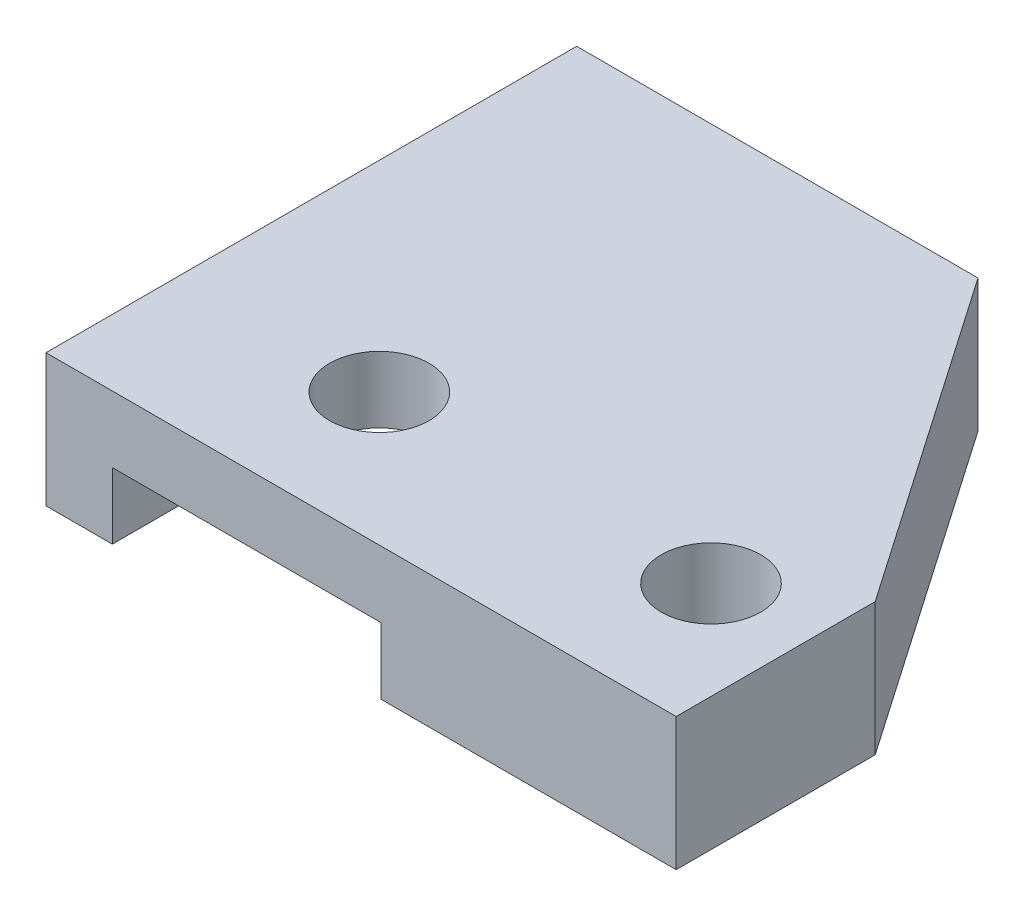
SolidWorks part; units mm, degrees
material "ABS"
ref_plane "Plan de face" through (0, 0, 0) normal (0, 0, 1) x (1, 0, 0)
ref_plane "Plan de dessus" through (0, 0, 0) normal (0, 1, 0) x (1, 0, 0)
ref_plane "Plan de droite" through (0, 0, 0) normal (1, 0, 0) x (0, 0, -1)
sketch "Esquisse1" plane through (0, 0, 0) normal (0, 0, 1) x (1, 0, 0)
  line L0 (10.1, -4) -> (19, -4)
  line L1 (0, 0) -> (19, 0)
  line L2 (0, 0) -> (0, -4)
  line L3 (0, -4) -> (2, -4)
  line L4 (19, 0) -> (19, -4)
  line L6 (2, -4) -> (2, -2)
  line L7 (2, -2) -> (10.1, -2)
  line L8 (10.1, -4) -> (10.1, -2)
  dimension "D1" = 2
  dimension "D2" = 2
  dimension "D3" = 8.1
  dimension "D4" = 19
  dimension "D5" = 8.9
extrude "Boss.-Extru.1" add sketch "Esquisse1" along normal blind 16
sketch "Esquisse2" plane through (0, 0, 0) normal (0, 1, 0) x (1, 0, 0)
  line L0 (19, -16) -> (0, -16) construction
  line L2 (19, -16) -> (19, 0) construction
  line L3 (2, -16) -> (10.1, -16) construction
  line L4 (12.1, 0) -> (19, 0)
  line L5 (19, 0) -> (0, 0) construction
  line L6 (19, 0) -> (19, -10)
  line L7 (19, -10) -> (12.1, 0)
  line L8 (10.1, -16) -> (10.1, 0) construction
  circle A0 centre (6.05, -12) radius 1.5
  circle A1 centre (16.05, -12) radius 1.5
  point P12 (6.05, -16)
  dimension "D1" = 3
  dimension "D2" = 4
  dimension "D3" = 2
  dimension "D4" = 2
  dimension "D5" = 2.95
  dimension "D6" = 10
extrude "Enlèv. mat.-Extru.1" cut sketch "Esquisse2" against normal through all
